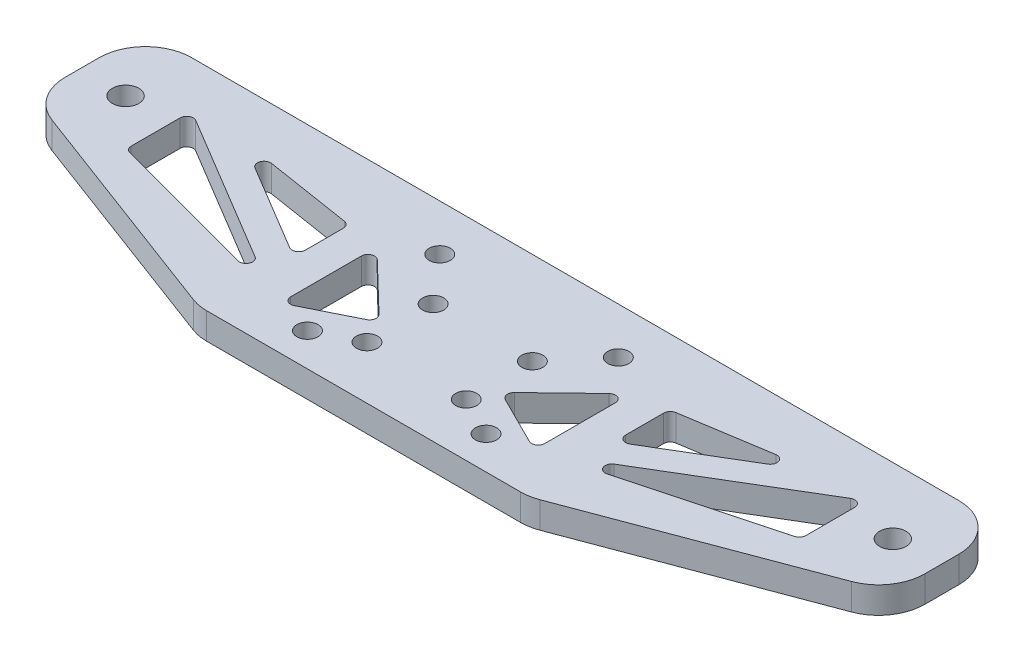
SolidWorks part; units mm, degrees
material "Thornel Mat VMA"
ref_plane "Front" through (0, 0, 0) normal (0, 0, 1) x (1, 0, 0)
ref_plane "Top" through (0, 0, 0) normal (0, 1, 0) x (1, 0, 0)
ref_plane "Right" through (0, 0, 0) normal (1, 0, 0) x (0, 0, -1)
sketch "草图1" plane through (0, 0, 0) normal (0, 1, 0) x (1, 0, 0)
  line L0 (0, 40.0348) -> (0, 0) construction
  line L1 (25, 0) -> (-25, 0)
  line L2 (-25, 0) -> (-65, 15)
  line L3 (-65, 15) -> (-65, 30)
  line L4 (-65, 30) -> (65, 30)
  line L5 (65, 15) -> (65, 30)
  line L6 (25, 0) -> (65, 15)
  point P9 (0, 30)
  dimension "D1" = 30
  dimension "D2" = 65
  dimension "D3" = 25
  dimension "D4" = 15
extrude "凸台-拉伸1" add sketch "草图1" along normal blind 4
sketch "草图2" plane through (0, 4, 0) normal (0, 1, 0) x (1, 0, 0)
  line L0 (0, 0) -> (0, 30) construction
  line L1 (65, 30) -> (-65, 30) construction
  line L2 (-7.5, 18) -> (-7.5, 8) construction
  line L3 (-7.5, 13) -> (7.5, 13) construction
  line L4 (7.5, 18) -> (7.5, 8) construction
  circle A0 centre (-7.5, 18) radius 1.6
  circle A3 centre (7.5, 18) radius 1.6
  circle A4 centre (-7.5, 8) radius 1.6
  circle A5 centre (7.5, 8) radius 1.6
  point P14 (0, 13)
  dimension "D1" = 3.2
  dimension "D2" = 10
  dimension "D3" = 7.5
  dimension "D4" = 17
extrude "切除-拉伸1" cut sketch "草图2" against normal through all
sketch "草图3" plane through (0, 4, 0) normal (0, 1, 0) x (1, 0, 0)
  line L0 (-65, 30) -> (-65, 15) construction
  line L1 (65, 30) -> (-65, 30) construction
  line L23 (-25, 0) -> (25, 0) construction
  line L24 (-51, 23.236) -> (-51, 15.8571)
  line L25 (-50.259, 14.8913) -> (-27.9213, 8.9003)
  line L26 (-27.1487, 10.7242) -> (-49.4864, 24.0941)
  line L27 (-38.7825, 22.3492) -> (-25.725, 14.5338)
  line L28 (-24.2114, 15.3918) -> (-24.2114, 21.1455)
  line L29 (-25.0554, 22.1333) -> (-38.113, 24.195)
  line L32 (-10.2291, 12.546) -> (-17.5171, 19.5762)
  line L33 (-65, 15) -> (-25, 0) construction
  line L34 (-13.5, 25) -> (-13.5, 5) construction
  line L35 (-19.2114, 18.8565) -> (-19.2114, 8.1823)
  line L36 (-17.7642, 7.2879) -> (-10.4762, 10.9319)
  line L37 (-13.5, 25) -> (-7.5, 18) construction
  line L38 (-7.5, 11.5643) -> (-9.2114, 11.5643) construction
  line L39 (0, 30) -> (0, 0) construction
  line L40 (7.5, 11.5643) -> (9.2114, 11.5643) construction
  line L41 (7.5, 20.5) -> (7.5, 10.5) construction
  line L42 (17.7642, 7.2879) -> (10.4762, 10.9319)
  line L43 (19.2114, 18.8565) -> (19.2114, 8.1823)
  line L44 (10.2291, 12.546) -> (17.5171, 19.5762)
  line L45 (25.0554, 22.1333) -> (38.113, 24.195)
  line L46 (24.2114, 15.3918) -> (24.2114, 21.1455)
  line L47 (38.7825, 22.3492) -> (25.725, 14.5338)
  line L48 (27.1487, 10.7242) -> (49.4864, 24.0941)
  line L49 (50.259, 14.8913) -> (27.9213, 8.9003)
  line L50 (51, 23.236) -> (51, 15.8571)
  line L51 (-7.5, 8) -> (-13.5, 5) construction
  circle A0 centre (-58, 22) radius 2
  arc A1 (-10.4762, 10.9319) -> (-10.2291, 12.546) centre (-10.9234, 11.8263) ccw
  arc A2 (-19.2114, 8.1823) -> (-17.7642, 7.2879) centre (-18.2114, 8.1823) ccw
  arc A3 (-19.2114, 18.8565) -> (-17.5171, 19.5762) centre (-18.2114, 18.8565) cw
  arc A4 (-24.2114, 21.1455) -> (-25.0554, 22.1333) centre (-25.2114, 21.1455) ccw
  arc A5 (-38.7825, 22.3492) -> (-38.113, 24.195) centre (-38.269, 23.2072) cw
  arc A6 (-25.725, 14.5338) -> (-24.2114, 15.3918) centre (-25.2114, 15.3918) ccw
  arc A7 (-27.1487, 10.7242) -> (-27.9213, 8.9003) centre (-27.6623, 9.8662) cw
  arc A8 (-51, 15.8571) -> (-50.259, 14.8913) centre (-50, 15.8571) ccw
  arc A9 (-51, 23.236) -> (-49.4864, 24.0941) centre (-50, 23.236) cw
  arc A10 (51, 23.236) -> (49.4864, 24.0941) centre (50, 23.236) ccw
  arc A11 (51, 15.8571) -> (50.259, 14.8913) centre (50, 15.8571) cw
  arc A12 (27.1487, 10.7242) -> (27.9213, 8.9003) centre (27.6623, 9.8662) ccw
  arc A13 (25.725, 14.5338) -> (24.2114, 15.3918) centre (25.2114, 15.3918) cw
  arc A14 (38.7825, 22.3492) -> (38.113, 24.195) centre (38.269, 23.2072) ccw
  arc A15 (24.2114, 21.1455) -> (25.0554, 22.1333) centre (25.2114, 21.1455) cw
  arc A16 (19.2114, 18.8565) -> (17.5171, 19.5762) centre (18.2114, 18.8565) ccw
  arc A17 (19.2114, 8.1823) -> (17.7642, 7.2879) centre (18.2114, 8.1823) cw
  arc A18 (10.4762, 10.9319) -> (10.2291, 12.546) centre (10.9234, 11.8263) cw
  circle A19 centre (58, 22) radius 2
  circle A20 centre (-13.5, 5) radius 1.6
  circle A21 centre (-13.5, 25) radius 1.6
  circle A22 centre (13.5, 5) radius 1.6
  circle A23 centre (13.5, 25) radius 1.6
  point P24 (-19.2114, 6.5643)
  point P32 (-19.2114, 21.2105)
  point P35 (-24.2114, 22)
  point P38 (-43.2114, 25)
  point P43 (-21, 7.044)
  point P46 (-51, 15.09)
  point P49 (-51, 25)
  point P86 (51, 25)
  point P87 (51, 15.09)
  point P88 (21, 7.044)
  point P89 (43.2114, 25)
  point P90 (24.2114, 22)
  point P91 (19.2114, 21.2105)
  point P92 (19.2114, 6.5643)
  dimension "D1" = 4
  dimension "D2" = 7
  dimension "D3" = 8
  dimension "D15" = 1
  dimension "D16" = 3.2
  dimension "D17" = 27
  dimension "D18" = 5
  dimension "D20" = 3.2
  dimension "D4" = 7
  dimension "D5" = 5
  dimension "D6" = 5
  dimension "D7" = 8
  dimension "D8" = 4
  dimension "D9" = 5
  dimension "D10" = 8
  dimension "D11" = 4
  dimension "D12" = 5
  dimension "D13" = 19
  dimension "D14" = 10
  dimension "D19" = 20
extrude "切除-拉伸2" cut sketch "草图3" against normal through all
sketch "草图4" plane through (0, 4, 0) normal (0, 1, 0) x (1, 0, 0)
  line L1 (-65, 30) -> (65, 30)
  line L2 (-65, 30) -> (-65, 32)
  line L3 (-65, 32) -> (65, 32)
  line L4 (65, 30) -> (65, 32)
  point P5 (65, 30)
  dimension "D1" = 2
extrude "凸台-拉伸2" add sketch "草图4" against normal blind 4
fillet "圆角1" radius 7 6 edges at (-25, 2, 0) (25, 2, 0) (65, 2, -15) (-65, 2, -15) (65, 2, -32) (-65, 2, -32)
